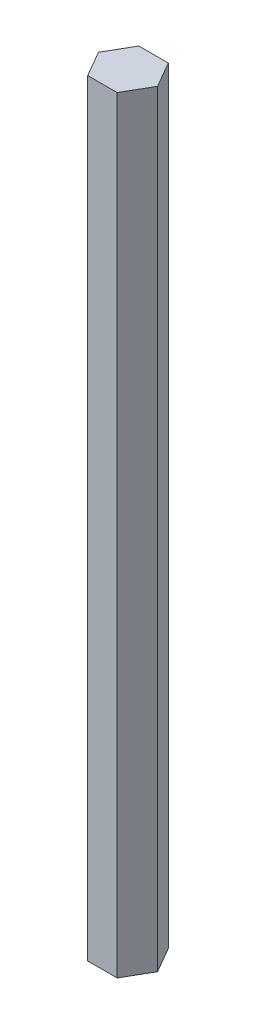
SolidWorks part; units mm, degrees
ref_plane "Front Plane" through (0, 0, 0) normal (0, 0, 1) x (1, 0, 0)
ref_plane "Top Plane" through (0, 0, 0) normal (0, 1, 0) x (1, 0, 0)
ref_plane "Right Plane" through (0, 0, 0) normal (1, 0, 0) x (0, 0, -1)
sketch "Sketch1" plane through (0, 0, 0) normal (0, 1, 0) x (1, 0, 0)
  line L1 (1.4434, -2.5) -> (2.8868, 0)
  line L2 (2.8868, 0) -> (1.4434, 2.5)
  line L3 (1.4434, 2.5) -> (-1.4434, 2.5)
  line L4 (-1.4434, 2.5) -> (-2.8868, 0)
  line L5 (-2.8868, 0) -> (-1.4434, -2.5)
  line L6 (-1.4434, -2.5) -> (1.4434, -2.5)
  circle A0 centre (0, 0) radius 2.5 construction
  dimension "D1" = 5
extrude "Boss-Extrude1" add sketch "Sketch1" along normal blind 75
